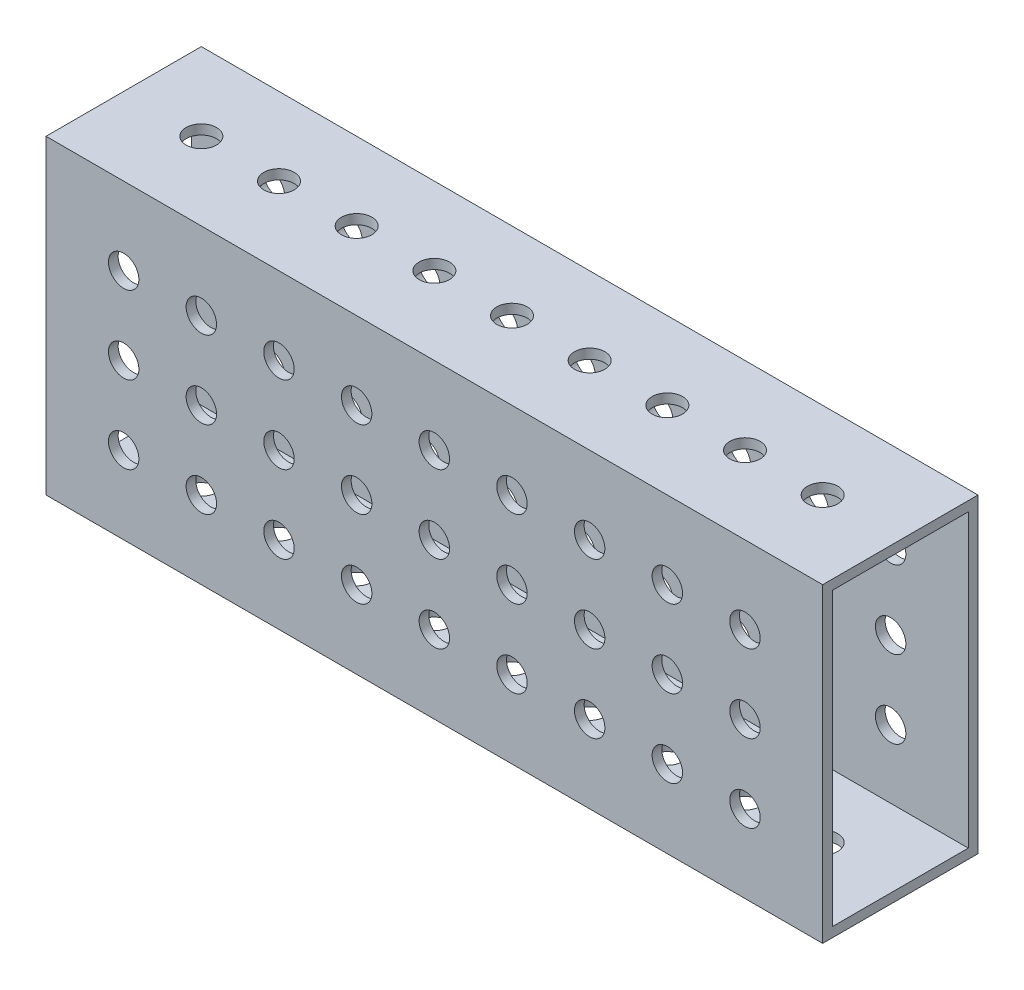
SolidWorks part; units mm, degrees
material "6061-T6 (SS)"
ref_plane "Front Plane" through (0, 0, 0) normal (0, 0, 1) x (1, 0, 0)
ref_plane "Top Plane" through (0, 0, 0) normal (0, 1, 0) x (1, 0, 0)
ref_plane "Right Plane" through (0, 0, 0) normal (1, 0, 0) x (0, 0, -1)
sketch "Sketch1" plane through (0, 0, 0) normal (0, 0, 1) x (1, 0, 0)
  line L1 (0, 0) -> (127, 0)
  line L2 (0, 0) -> (0, 50.8)
  line L3 (0, 50.8) -> (127, 50.8)
  line L4 (127, 0) -> (127, 50.8)
  dimension "D1" = 127
  dimension "D2" = 50.8
extrude "Boss-Extrude1" add sketch "Sketch1" along normal mid plane 25.4
shell "Shell1" thickness 1.5875
sketch "Sketch2" plane through (0, 0, -12.7) normal (0, 0, -1) x (-1, 0, 0)
  line L0 (-114.3, 12.7) -> (-114.3, 38.1) construction
  line L1 (0, 0) -> (-127, 0) construction
  line L2 (-127, 0) -> (-127, 50.8) construction
  circle A0 centre (-114.3, 38.1) radius 2.4892
  circle A1 centre (-114.3, 25.4) radius 2.4892
  circle A2 centre (-114.3, 12.7) radius 2.4892
  dimension "D1" = 4.9784
  dimension "D2" = 12.7
  dimension "D3" = 12.7
  dimension "D4" = 12.7
extrude "Cut-Extrude1" cut sketch "Sketch2" against normal through all
sketch "Sketch3" plane through (0, 50.8, 0) normal (0, 1, 0) x (1, 0, 0)
  line L0 (127, 12.7) -> (0, 12.7) construction
  line L1 (127, -12.7) -> (127, 12.7) construction
  circle A0 centre (114.3, 0) radius 2.4892
  dimension "D3" = 4.9784
  dimension "D1" = 12.7
  dimension "D2" = 12.7
extrude "Cut-Extrude2" cut sketch "Sketch3" against normal through all
pattern_linear "LPattern1" count 9 spacing 12.7 along (-1, 0, 0) of "Cut-Extrude1", "Cut-Extrude2"
sketch "Sketch4" [suppressed] plane through (0, 0, -12.7) normal (0, 0, -1) x (-1, 0, 0)
  line L0 (-107.95, 50.8) -> (-81.28, 31.75)
  line L1 (-127, 50.8) -> (0, 50.8) construction
  line L2 (-81.28, 31.75) -> (-45.72, 31.75)
  line L3 (-45.72, 31.75) -> (-19.05, 50.8)
  line L4 (-127, 0) -> (-127, 50.8) construction
  line L5 (0, 50.8) -> (0, 0) construction
  dimension "D1" = 19.05
  dimension "D2" = 35.56
  dimension "D3" = 19.05
  dimension "D4" = 19.05
extrude "Cut-Extrude3" [suppressed] cut sketch "Sketch4" against normal through all and the other way through all
